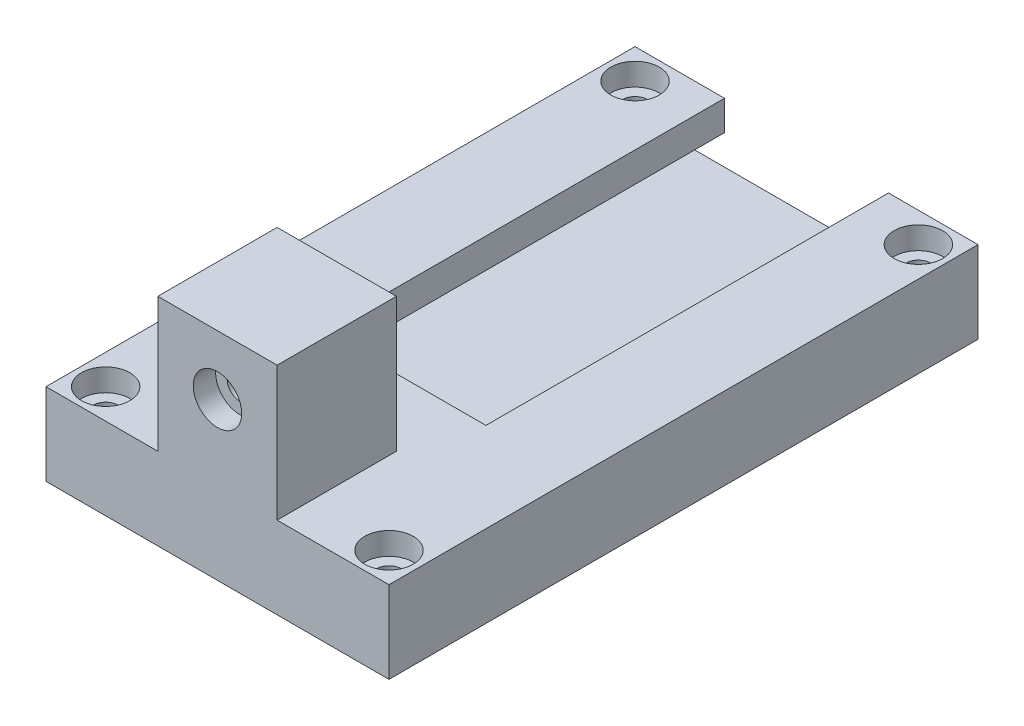
SolidWorks part; units mm, degrees
ref_plane "Спереди" through (0, 0, 0) normal (0, 0, 1) x (1, 0, 0)
ref_plane "Сверху" through (0, 0, 0) normal (0, 1, 0) x (1, 0, 0)
ref_plane "Справа" through (0, 0, 0) normal (1, 0, 0) x (0, 0, -1)
sketch "Эскиз1" plane through (0, 0, 0) normal (0, 0, 1) x (1, 0, 0)
  line L0 (0, 0) -> (0, 11)
  line L1 (0, 11) -> (12, 11)
  line L2 (12, 11) -> (12, 7)
  line L3 (12, 7) -> (8, 7)
  line L4 (8, 7) -> (8, 3)
  line L5 (8, 3) -> (38, 3)
  line L6 (38, 3) -> (38, 7)
  line L7 (38, 7) -> (34, 7)
  line L8 (34, 7) -> (34, 11)
  line L9 (34, 11) -> (46, 11)
  line L10 (46, 11) -> (46, 0)
  line L11 (46, 0) -> (0, 0)
  dimension "D1" = 4
  dimension "D2" = 4
  dimension "D3" = 22
  dimension "D4" = 8
  dimension "D5" = 4
  dimension "D6" = 4
  dimension "D7" = 30
  dimension "D8" = 46
  dimension "D9" = 4
  dimension "D10" = 3
  dimension "D11" = 4
extrude "Бобышка-Вытянуть1" add sketch "Эскиз1" along normal blind 54
sketch "Эскиз2" plane through (0, 0, 54) normal (0, 0, 1) x (1, 0, 0)
  line L0 (0, 11) -> (12, 11)
  line L1 (12, 11) -> (34, 11)
  line L2 (34, 11) -> (46, 11)
  line L3 (46, 11) -> (46, 0)
  line L4 (46, 0) -> (0, 0)
  line L5 (0, 0) -> (0, 11)
extrude "Бобышка-Вытянуть2" add sketch "Эскиз2" along normal blind 25
hole_wizard "Цековка для винта с внутренним шестигранником M31" positions "Эскиз4" profile "Эскиз5" counterbore size "M3" standard "Ansi Metric"
sketch "Эскиз4" plane through (0, 11, 0) normal (0, 1, 0) x (1, 0, 0)
  line L0 (42, -75) -> (42, -4) construction
  line L2 (46, -79) -> (46, 0) construction
  line L3 (46, 0) -> (34, 0) construction
  line L4 (57.5385, -4) -> (4, -4) construction
  line L6 (4, -4) -> (4, -75) construction
  line L8 (0, -79) -> (0, 0) construction
  line L9 (42, -75) -> (4, -75) construction
  line L11 (46, -79) -> (0, -79) construction
  point P0 (42, -4)
  point P2 (42, -75)
  point P4 (4, -4)
  point P6 (4, -75)
  point P43 (0, 0)
  point P44 (4, -64.1685)
  point P45 (4.7143, -64.6827)
  point P46 (36.8538, -64.029)
  dimension "D1" = 4
  dimension "D2" = 4
  dimension "D3" = 4
  dimension "D4" = 4
  dimension "D5" = 4
sketch "Эскиз5" plane through (42, 11, 4) normal (1, 0, 0) x (0, 0, 1)
  line L0 (0, 0) -> (0, 12.0205)
  line L1 (0, 12.0205) -> (1.7, 10.999)
  line L2 (1.7, 10.999) -> (1.7, 3)
  line L3 (1.7, 3) -> (3.25, 3)
  line L4 (3.25, 3) -> (3.25, 0)
  line L5 (3.25, 0) -> (0, 0)
  line L10 (0, 12.0205) -> (-1.7, 10.999) construction
  line L11 (0, -6.35) -> (0, 17.464) construction
  point P6 (0, 35.3828)
  point P7 (0, 17.464)
  dimension "Диаметр отверстия" = 3.4
  dimension "Глубина отверстия" = 10.999
  dimension "Диаметр цековки" = 6.5
  dimension "Глубина цековки" = 3
  dimension "Угол заточки сверла" = 118
sketch "Эскиз6" plane through (0, 11, 0) normal (0, 1, 0) x (1, 0, 0)
  line L0 (15, -79) -> (15, -63)
  line L1 (46, -79) -> (0, -79) construction
  line L2 (15, -63) -> (31, -63)
  line L3 (31, -63) -> (31, -79)
  line L4 (31, -79) -> (15, -79)
  line L5 (23, -79) -> (23, -54) construction
  line L6 (34, -54) -> (12, -54) construction
  point P10 (23, -54)
  point P11 (23, -54)
  point P12 (23, -79)
  dimension "D1" = 16
  dimension "D2" = 16
extrude "Бобышка-Вытянуть3" add sketch "Эскиз6" along normal blind 18
hole_wizard "Цековка для винта с внутренним шестигранником M32" positions "Эскиз7" profile "Эскиз8" counterbore size "M3" standard "Ansi Metric" end condition through all
sketch "Эскиз7" plane through (0, 0, 79) normal (0, 0, 1) x (1, 0, 0)
  line L0 (15, 29) -> (15, 11) construction
  line L1 (15, 29) -> (31, 29) construction
  point P0 (23, 21)
  dimension "D1" = 8
  dimension "D2" = 8
sketch "Эскиз8" plane through (23, 21, 79) normal (1, 0, 0) x (0, -1, 0)
  line L0 (0, 0) -> (0, 79)
  line L1 (0, 79) -> (1.7, 79)
  line L3 (1.7, 79) -> (1.7, 3)
  line L4 (1.7, 3) -> (3.25, 3)
  line L5 (3.25, 3) -> (3.25, 0)
  line L7 (3.25, 0) -> (0, 0)
  line L11 (0, -6.35) -> (0, 107.95) construction
  dimension "Диаметр сквозного отверстия" = 3.4
  dimension "Глубина сквозного отверстия" = 79
  dimension "Диаметр цековки" = 6.5
  dimension "Глубина цековки" = 3
